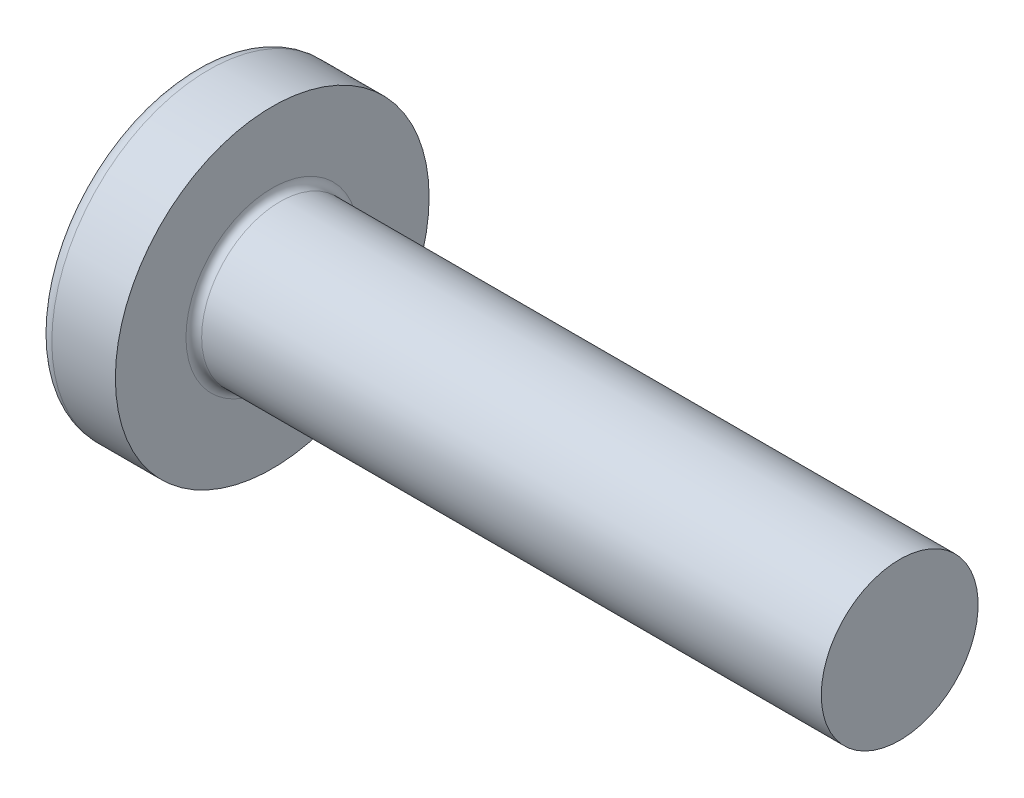
SolidWorks part; units mm, degrees
ref_plane "Plane1" through (0, 0, 0) normal (0, 0, 1) x (1, 0, 0)
ref_plane "Plane2" through (0, 0, 0) normal (0, 1, 0) x (1, 0, 0)
ref_plane "Plane3" through (0, 0, 0) normal (1, 0, 0) x (0, 0, -1)
sketch "BodySke" plane through (0, 0, 0) normal (0, 0, 1) x (1, 0, 0)
  line L0 (1.6, 1) -> (1.6, 2)
  line L1 (1.8, 6.35) -> (1.8, -3.175) construction
  line L2 (-25.4, 0) -> (127, 0) construction
  line L3 (9.6, 0) -> (0, 0)
  line L4 (1.6, 1) -> (9.6, 1)
  line L5 (9.6, 1) -> (9.6, 0)
  line L6 (0.79, 2) -> (1.6, 2)
  line L8 (3.6, 6.35) -> (3.6, -3.175) construction
  arc A0 (0.6464, 1.9285) -> (0, 0) centre (3.2, 0) ccw
  arc A2 (0.6464, 1.9285) -> (0.79, 2) centre (0.79, 1.82) cw
  dimension "Head_crown_rad" = 3.2
  dimension "Head_fillet_rad" = 0.18
  dimension "Head_ht" = 1.6
  dimension "Head_dia" = 4
  dimension "Advance" = 0.4
  dimension "Thread_nom" = 6
  dimension "Diameter" = 2
revolve "Base-Revolve" add sketch "BodySke"
cosmetic thread "ThreadCosmetic" [suppressed]
fillet "Fillet1" radius 0.1 1 edges at (1.6, 0, 1)
sketch "Sketch3" plane through (0, 0, 0) normal (1, 0, 0) x (0, 0, -1)
  line L0 (0.24, -1.05) -> (-0.24, -1.05)
  line L1 (0.24, -1.05) -> (0.24, 1.05)
  line L2 (-0.24, 1.05) -> (0.24, 1.05)
  line L3 (-0.24, 1.05) -> (-0.24, -1.05)
  dimension "Cross_dia" = 2.1
  dimension "D1" = 1.05
  dimension "Cross_width" = 0.48
  dimension "D2" = 0.24
ref_plane "Plane4" through (1.42, 0, 0) normal (1, 0, 0) x (0, 0, -1)
sketch "Sketch4" plane through (1.42, 0, 0) normal (1, 0, 0) x (0, 0, -1)
  line L0 (0.24, -0.342) -> (-0.24, -0.342)
  line L1 (0.24, -0.342) -> (0.24, 0.342)
  line L2 (-0.24, 0.342) -> (0.24, 0.342)
  line L3 (-0.24, 0.342) -> (-0.24, -0.342)
  dimension "D1" = 0.48
  dimension "D2" = 0.684
  dimension "D3" = 0.24
  dimension "D4" = 0.342
loft "Recess" cut profiles "Sketch3", "Sketch4"
pattern_circular "RecPat" count 2 every 90 about axis through (0, 0, 0) along (1, 0, 0) of "Recess"
sketch "RecCorSke" plane through (0, 0, 0) normal (0, 0, 1) x (1, 0, 0)
  line L0 (-3.175, 0) -> (15.875, 0) construction
  line L1 (-25.4, 0) -> (127, 0) construction
  line L2 (0, 0) -> (0, 0.4548)
  line L3 (0, 0.4548) -> (1.42, 0.3555)
  line L4 (1.42, 0.3555) -> (1.5355, 0)
  line L5 (1.5355, 0) -> (0, 0)
  dimension "Diameter" = 0.711
  dimension "Depth" = 1.42
  dimension "Draft_angle" = 4
  dimension "Bottom_angle" = 18
revolve "RecessCore" cut sketch "RecCorSke" angle 360 about L0
sketch "ThdSchSke" plane through (0, 0, 0) normal (0, 0, 1) x (1, 0, 0)
  line L0 (3.6, -0.774) -> (3.4418, -1)
  line L1 (3.6, -0.774) -> (3.7582, -1)
  line L2 (3.7582, -1) -> (3.7582, -1.25)
  line L3 (-3.175, 0) -> (5.1513, 0) construction
  line L5 (3.7582, -1.25) -> (3.4418, -1.25)
  line L6 (3.4418, -1.25) -> (3.4418, -1)
  dimension "Diameter" = 2
  dimension "SideAngle" = 55
  dimension "VeeAngle" = 70
  dimension "Thread_minor" = 1.548
  dimension "Overcut" = 2.5
  dimension "Start" = 3.6
revolve "ThreadSchematic" [suppressed] cut sketch "ThdSchSke" angle 360 about L3
pattern_linear "ThdSchPat" [suppressed]
equation "\"D1@Sketch3\" = \"Cross_dia@Sketch3\" / 2"
equation "\"D2@Sketch3\" = \"Cross_width@Sketch3\" / 2"
equation "\"Depth@RecCorSke\" = \"Cross_depth@Plane4\""
equation "\"D1@Sketch4\" = \"Cross_width@Sketch3\""
equation "\"D2@Sketch4\" = \"Cross_dia@Sketch3\" - 2.0 * \"Cross_depth@Plane4\" * tan(26.5  * 0.017453292)"
equation "\"D3@Sketch4\" = \"D1@Sketch4\" / 2"
equation "\"D4@Sketch4\" = \"D2@Sketch4\" / 2"
equation "\"Thread_length@ThreadCosmetic\" = ((sgn( (\"Length@BodySke\" - \"Advance@BodySke\" * 2.0 ) - \"Thread_nom@BodySke\" )-1)*( (\"Length@BodySke\" - \"Advance@BodySke\" * 2.0 ) - \"Thread_nom@BodySke\" ))/-2+ \"Thread_nom@BodySke\""
equation "\"Thread_minor@ThdSchSke\" = \"Thread_minor@ThreadCosmetic\""
equation "\"Diameter@ThdSchSke\" = \"Diameter@BodySke\""
equation "\"Overcut@ThdSchSke\" = \"Diameter@BodySke\" * 1.25"
equation "\"Start@ThdSchSke\" = \"Head_ht@BodySke\" + \"Length@BodySke\" - \"Thread_length@ThreadCosmetic\"  '---Non-countersunk---"
equation "\"Num_threads@ThdSchPat\" = int( \"Thread_length@ThreadCosmetic\" / \"Advance@BodySke\" + 0.999 )  + 1"
equation "\"Advance@ThdSchPat\" = \"Thread_length@ThreadCosmetic\" /  (\"Num_threads@ThdSchPat\" - 1) 'relax it"
